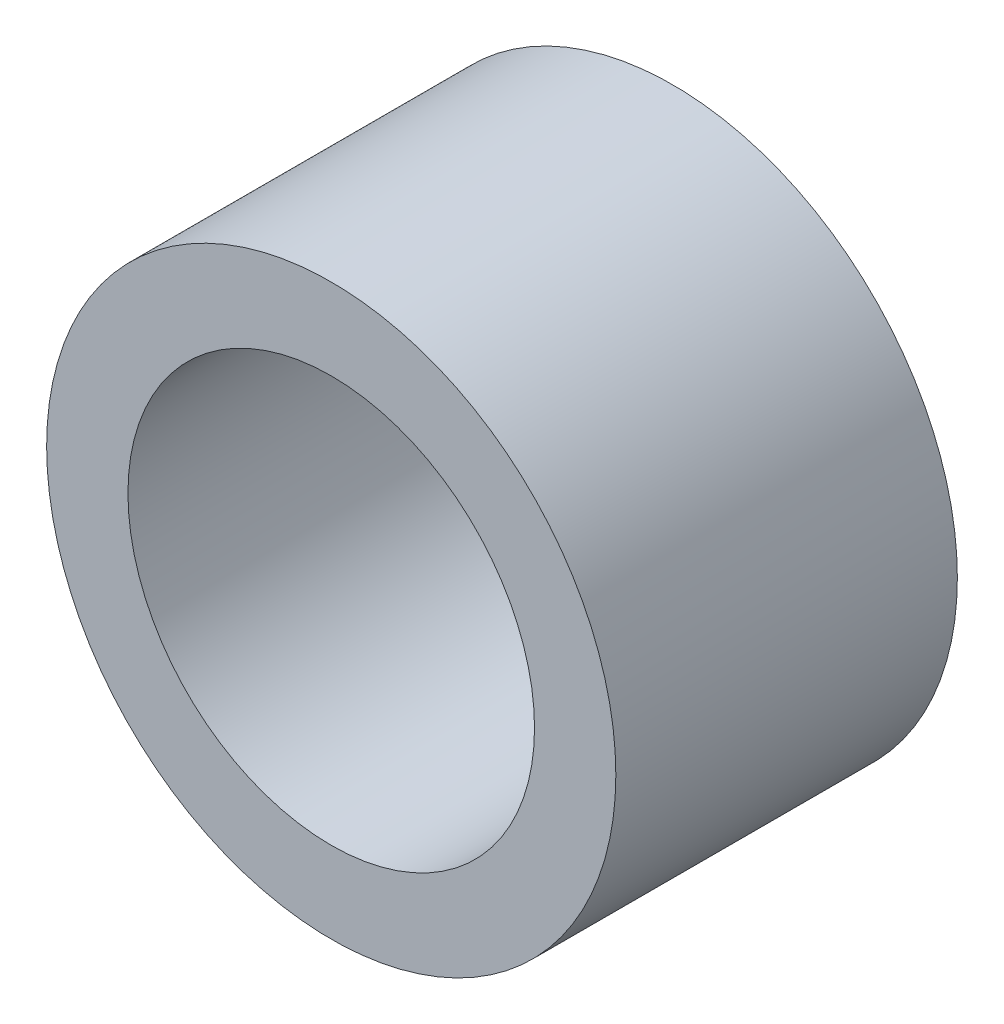
SolidWorks part; units mm, degrees
material "Alloy Steel"
ref_plane "Front Plane" through (0, 0, 0) normal (0, 0, 1) x (1, 0, 0)
ref_plane "Top Plane" through (0, 0, 0) normal (0, 1, 0) x (1, 0, 0)
ref_plane "Right Plane" through (0, 0, 0) normal (1, 0, 0) x (0, 0, -1)
sketch "Sketch2" plane through (0, 0, 0) normal (0, 0, 1) x (1, 0, 0)
  circle A0 centre (0, 0) radius 17.5
  circle A1 centre (0, 0) radius 12.5
extrude "Boss-Extrude1" add sketch "Sketch2" along normal blind 21
